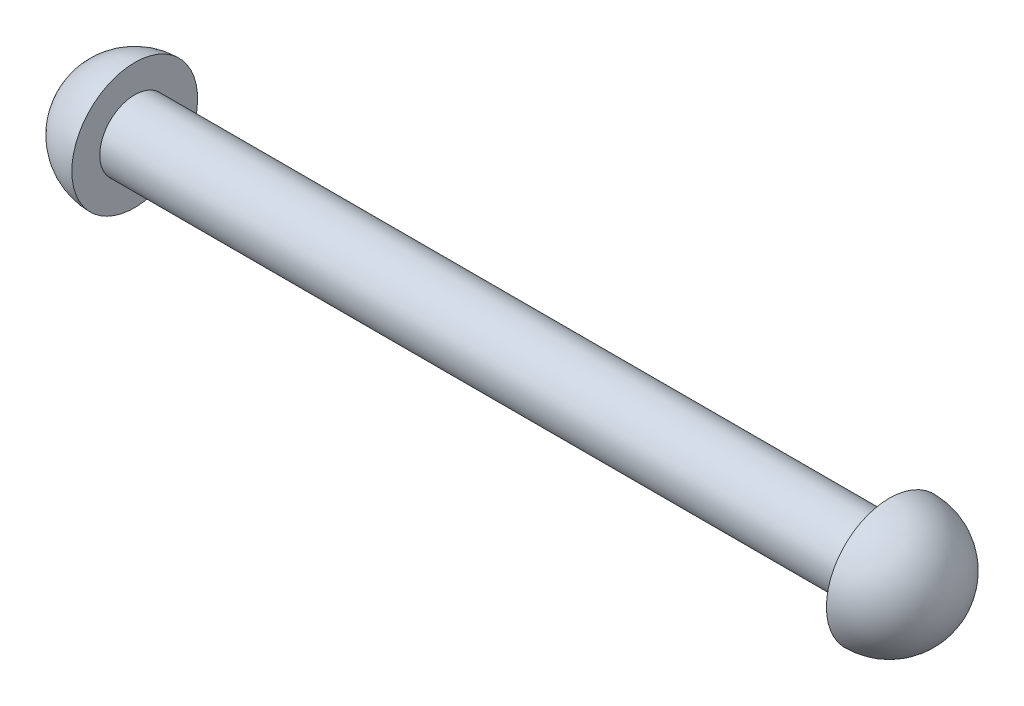
SolidWorks part; units mm, degrees
ref_plane "Front Plane" through (0, 0, 0) normal (0, 0, 1) x (1, 0, 0)
ref_plane "Top Plane" through (0, 0, 0) normal (0, 1, 0) x (1, 0, 0)
ref_plane "Right Plane" through (0, 0, 0) normal (1, 0, 0) x (0, 0, -1)
sketch "Sketch1" plane through (0, 0, 0) normal (0, 0, 1) x (1, 0, 0)
  line L0 (-34.29, -1.5875) -> (-40.005, -1.5875)
  line L1 (-34.29, -1.5875) -> (34.29, -1.5875)
  line L2 (-34.29, -1.5875) -> (-34.29, 1.5875)
  line L3 (-34.29, 1.5875) -> (34.29, 1.5875)
  line L4 (34.29, -1.5875) -> (34.29, 1.5875)
  line L5 (-34.29, -1.5875) -> (34.29, 1.5875) construction
  line L6 (-34.29, 1.5875) -> (34.29, -1.5875) construction
  line L7 (-34.29, 1.5875) -> (-34.29, 4.1275)
  line L8 (0, 0) -> (0, 7.7388) construction
  line L9 (34.29, 1.5875) -> (34.29, 4.1275)
  line L10 (34.29, -1.5875) -> (40.005, -1.5875)
  arc A0 (-34.29, 4.1275) -> (-40.005, -1.5875) centre (-34.29, -1.5875) ccw
  arc A1 (34.29, 4.1275) -> (40.005, -1.5875) centre (34.29, -1.5875) cw
  point P0 (0, 0)
  dimension "D3" = 11.43
  dimension "D1" = 3.175
  dimension "D2" = 68.58
revolve "Revolve1" add sketch "Sketch1" angle 360 about L1
